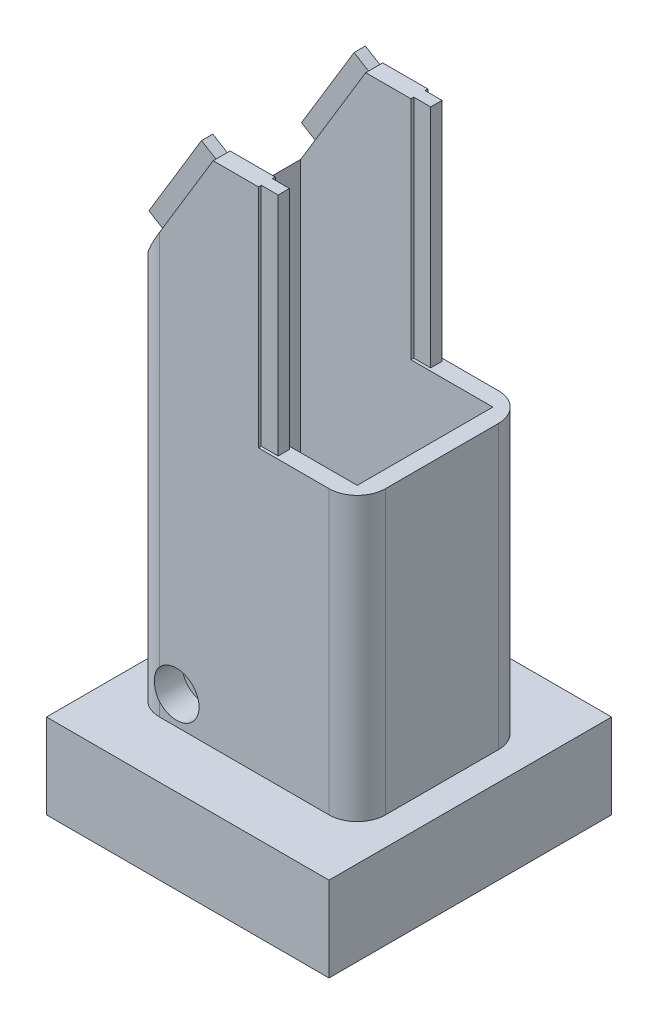
SolidWorks part; units mm, degrees
ref_plane "Front Plane" through (0, 0, 0) normal (0, 0, 1) x (1, 0, 0)
ref_plane "Top Plane" through (0, 0, 0) normal (0, 1, 0) x (1, 0, 0)
ref_plane "Right Plane" through (0, 0, 0) normal (1, 0, 0) x (0, 0, -1)
sketch "Sketch1" plane through (0, 0, 0) normal (0, 1, 0) x (1, 0, 0)
  line L1 (-20, -15) -> (20, -15)
  line L2 (-20, -15) -> (-20, 15)
  line L3 (-20, 15) -> (20, 15)
  line L4 (20, -15) -> (20, 15)
  line L5 (-20, -15) -> (20, 15) construction
  line L6 (-20, 15) -> (20, -15) construction
  point P0 (0, 0)
  dimension "D1" = 40
  dimension "D2" = 30
extrude "Boss-Extrude1" add sketch "Sketch1" along normal blind 90
shell "Shell1" thickness 3
fillet "Fillet1" radius 5 4 edges at (20, 45, -15) (20, 45, 15) (-20, 45, -15) (-20, 45, 15)
sketch "Sketch2" plane through (0, 0, 0) normal (0, 0, 1) x (1, 0, 0)
  line L0 (-5.5, 90) -> (-20, 66)
  line L1 (17, 90) -> (-17, 90) construction
  line L2 (-20, 90) -> (-20, 0) construction
  line L3 (-20, 66) -> (-20, 90)
  line L4 (-20, 90) -> (-5.5, 90)
  dimension "D1" = 5.5
  dimension "D2" = 66
extrude "Cut-Extrude1" cut sketch "Sketch2" against normal through all both and the other way through all
sketch "Sketch3" plane through (0, 0, 0) normal (0, 0, 1) x (1, 0, 0)
  line L1 (20, 90) -> (2.5, 90)
  line L2 (20, 90) -> (20, 50)
  line L3 (20, 50) -> (2.5, 50)
  line L4 (2.5, 90) -> (2.5, 50)
  dimension "D1" = 40
  dimension "D2" = 17.5
extrude "Cut-Extrude2" cut sketch "Sketch3" against normal through all both and the other way through all
sketch "Sketch5" plane through (2.5, 0, 0) normal (1, 0, 0) x (0, 0, -1)
  line L0 (-13.5, 90) -> (-13.5, 50) construction
  line L1 (-12, 90) -> (-15, 90) construction
  line L2 (-12, 50) -> (-15, 50) construction
  line L4 (-14.5, 90) -> (-12.5, 90)
  line L5 (-14.5, 90) -> (-14.5, 50)
  line L6 (-14.5, 50) -> (-12.5, 50)
  line L7 (-12.5, 90) -> (-12.5, 50)
  dimension "D1" = 2
extrude "Boss-Extrude2" add sketch "Sketch5" along normal blind 3
mirror "Mirror1" about plane through (0, 0, 0) normal (0, 0, 1) of "Boss-Extrude2"
sketch "Sketch6" plane through (-43.8639, 26.5011, 0) normal (-0.8559, 0.5171, 0) x (0, 0, 1)
  line L0 (-13.5, 74.1883) -> (-13.5, 56.1883) construction
  line L1 (-15, 74.1883) -> (-12, 74.1883) construction
  line L3 (-14.5, 74.1883) -> (-12.5, 74.1883)
  line L4 (-14.5, 74.1883) -> (-14.5, 56.1883)
  line L5 (-14.5, 56.1883) -> (-12.5, 56.1883)
  line L6 (-12.5, 74.1883) -> (-12.5, 56.1883)
  dimension "D1" = 18
  dimension "D2" = 2
extrude "Boss-Extrude3" add sketch "Sketch6" along normal blind 3
mirror "Mirror2" about plane through (0, 0, 0) normal (0, 0, 1) of "Boss-Extrude3"
sketch "Sketch8" plane through (0, 0, 0) normal (0, 1, 0) x (1, 0, 0)
  line L1 (-25, -25) -> (25, -25)
  line L2 (-25, -25) -> (-25, 25)
  line L3 (-25, 25) -> (25, 25)
  line L4 (25, -25) -> (25, 25)
  line L5 (-25, -25) -> (25, 25) construction
  line L6 (-25, 25) -> (25, -25) construction
  point P0 (0, 0)
  dimension "D1" = 50
  dimension "D2" = 50
extrude "Boss-Extrude4" add sketch "Sketch8" against normal blind 15
sketch "Sketch10" plane through (-25, 0, 0) normal (-1, 0, 0) x (0, 0, 1)
  line L0 (-25, -7.5) -> (25, -7.5) construction
  line L1 (-22.5, -12.5) -> (22.5, -12.5)
  line L2 (-22.5, -12.5) -> (-22.5, -2.5)
  line L3 (-22.5, -2.5) -> (22.5, -2.5)
  line L4 (22.5, -12.5) -> (22.5, -2.5)
  line L5 (-22.5, -12.5) -> (22.5, -2.5) construction
  line L6 (-22.5, -2.5) -> (22.5, -12.5) construction
  line L7 (-25, -15) -> (-25, 0) construction
  line L8 (25, -15) -> (25, 0) construction
  line L9 (0, 0) -> (0, -15) construction
  line L10 (-25, -15) -> (25, -15) construction
  point P0 (0, -7.5)
  dimension "D1" = 45
  dimension "D2" = 10
extrude "Cut-Extrude4" cut sketch "Sketch10" against normal blind 37.5
sketch "Sketch15" plane through (0, 0, -12) normal (0, 0, 1) x (1, 0, 0)
  line L1 (-17, 0) -> (-7, 0)
  line L2 (-17, 0) -> (-17, 10)
  line L3 (-17, 10) -> (-7, 10)
  line L4 (-7, 0) -> (-7, 10)
  dimension "D1" = 10
  dimension "D2" = 10
extrude "Boss-Extrude5" add sketch "Sketch15" along normal up to next
sketch "Sketch20" plane through (0, 0, -15) normal (0, 0, -1) x (-1, 0, 0)
  line L0 (17, 70.9655) -> (17, 10) construction
  line L2 (-17, 0) -> (7, 0) construction
  circle A0 centre (12, 5) radius 2
  dimension "D2" = 5
  dimension "D3" = 4
  dimension "D1" = 5
extrude "Cut-Extrude8" cut sketch "Sketch20" against normal through all both and the other way through all
sketch "Sketch21" plane through (0, 0, -15) normal (0, 0, -1) x (-1, 0, 0)
  circle A0 centre (12, 5) radius 4
  dimension "D1" = 8
extrude "Cut-Extrude9" cut sketch "Sketch21" against normal blind 5
mirror "Mirror3" about plane through (0, 0, 0) normal (0, 0, 1) of "Cut-Extrude9"
